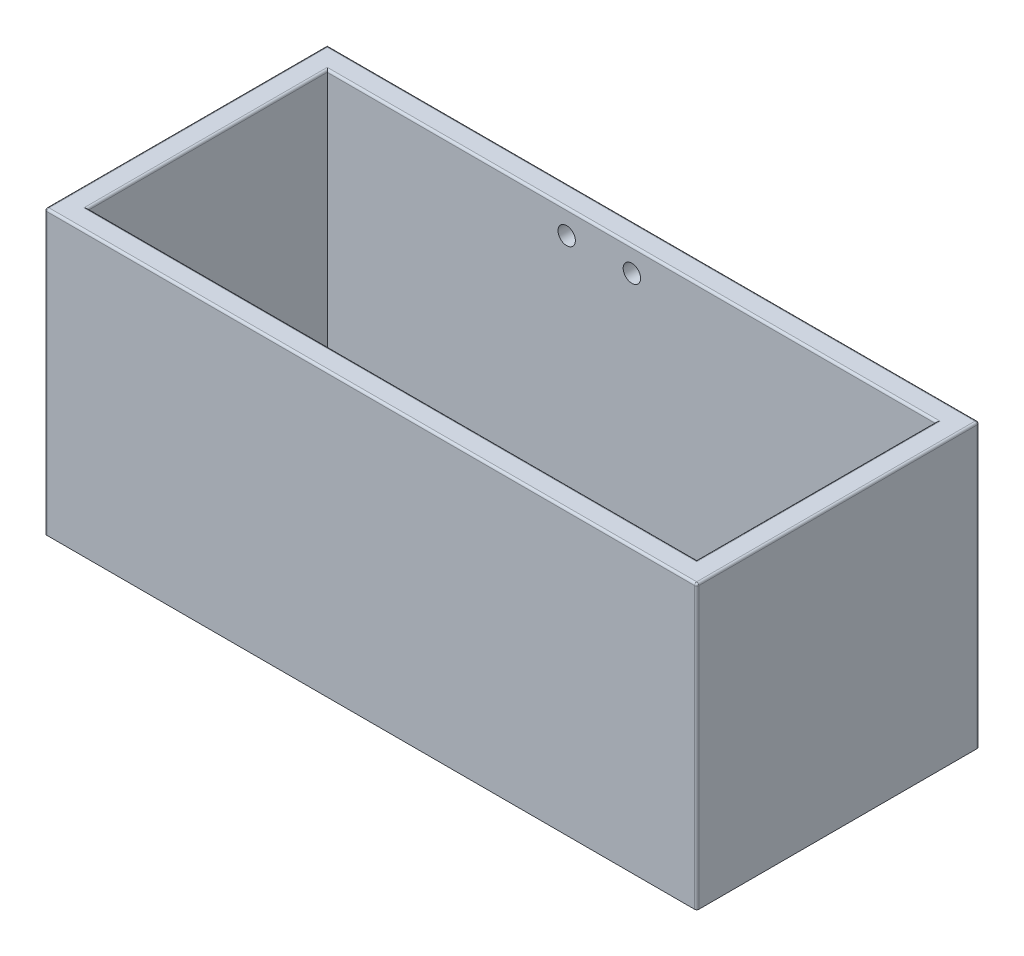
SolidWorks part; units mm, degrees
ref_plane "Plan de face" through (0, 0, 0) normal (0, 0, 1) x (1, 0, 0)
ref_plane "Plan de dessus" through (0, 0, 0) normal (0, 1, 0) x (1, 0, 0)
ref_plane "Plan de droite" through (0, 0, 0) normal (1, 0, 0) x (0, 0, -1)
sketch "Esquisse1" plane through (0, 0, 0) normal (0, 0, 1) x (1, 0, 0)
  line L0 (-114.2824, 0) -> (185.7176, 0)
  line L1 (185.7176, 0) -> (185.7176, 130)
  line L2 (185.7176, 130) -> (-114.2824, 130)
  line L3 (-114.2824, 130) -> (-114.2824, 0)
extrude "Boss.-Extru.2" add sketch "Esquisse1" along normal blind 130
sketch "Esquisse6" plane through (0, 130, 0) normal (0, 1, 0) x (1, 0, 0)
  line L0 (185.7176, 0) -> (-114.2824, 0) construction
  line L1 (-104.2824, -10) -> (175.7176, -10)
  line L2 (-104.2824, -10) -> (-104.2824, -120)
  line L3 (-104.2824, -120) -> (175.7176, -120)
  line L4 (175.7176, -10) -> (175.7176, -120)
  line L5 (-114.2824, -130) -> (-114.2824, 0) construction
  line L6 (185.7176, -130) -> (-114.2824, -130) construction
  line L7 (185.7176, -130) -> (185.7176, 0) construction
  dimension "D1" = 10
  dimension "D2" = 10
  dimension "D3" = 10
  dimension "D4" = 10
extrude "Enlèv. mat.-Extru.1" cut sketch "Esquisse6" against normal blind 120
fillet "Congé2" radius 1 2 edges at (35.7176, 130, 10) (-104.2824, 130, 65)
fillet "Congé3" radius 1 1 edges at (35.2176, 130, 120)
fillet "Congé4" radius 1 1 edges at (175.7176, 130, 65)
fillet "Congé5" radius 1 2 edges at (-114.2824, 130, 65) (35.7176, 130, 0)
fillet "Congé6" radius 1 3 edges at (-114.2824, 64.5, 130) (-113.9895, 129.7071, 130) (36.2176, 130, 130)
fillet "Congé7" radius 1 5 edges at (185.7176, 64.5, 130) (185.7176, 129.7071, 129.7071) (185.7176, 64.5, 0) (185.7176, 129.7071, 0.2929) (185.7176, 130, 65)
sketch "Esquisse7" plane through (0, 0, 10) normal (0, 0, 1) x (1, 0, 0)
  line L0 (175.7176, 129) -> (-104.2824, 129) construction
  circle A0 centre (5.8725, 119) radius 4
  circle A1 centre (35.8725, 119.0012) radius 4
  point P6 (35.7176, 129)
  point P9 (195.7613, 124.1635)
  dimension "D1" = 10
  dimension "D2" = 10
  dimension "D3" = 30
extrude "Enlèv. mat.-Extru.2" cut sketch "Esquisse7" against normal through all
